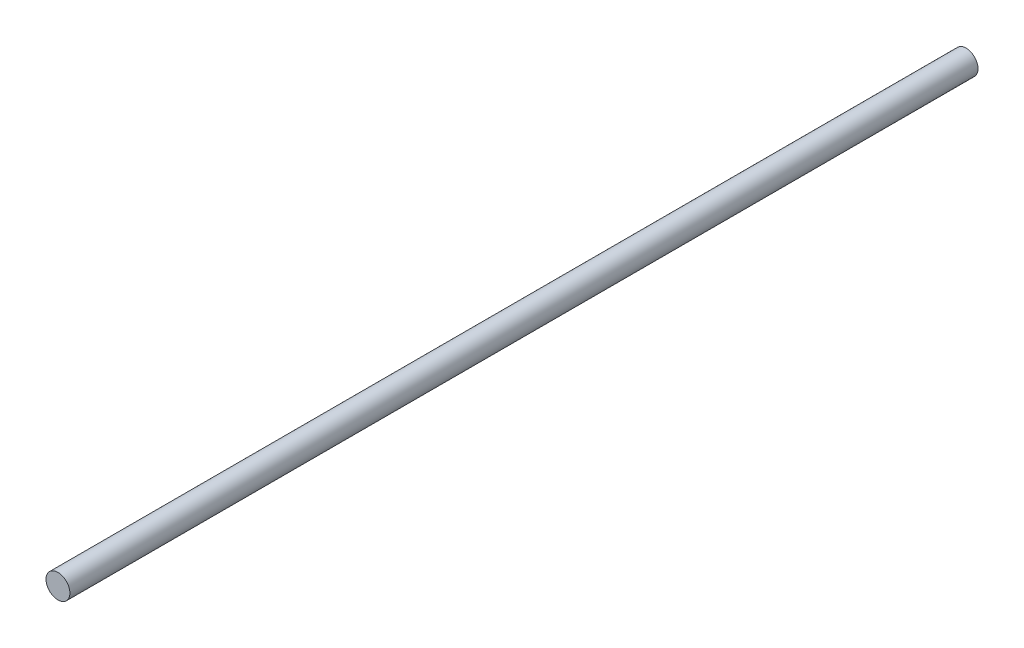
SolidWorks part; units mm, degrees
ref_plane "Plan de face" through (0, 0, 0) normal (0, 0, 1) x (1, 0, 0)
ref_plane "Plan de dessus" through (0, 0, 0) normal (0, 1, 0) x (1, 0, 0)
ref_plane "Plan de droite" through (0, 0, 0) normal (1, 0, 0) x (0, 0, -1)
sketch "Esquisse1" plane through (0, 0, 0) normal (0, 0, 1) x (1, 0, 0)
  circle A0 centre (0, 0) radius 3.175
  dimension "D1" = 6.35
extrude "Boss.-Extru.1" add sketch "Esquisse1" along normal blind 241.3
